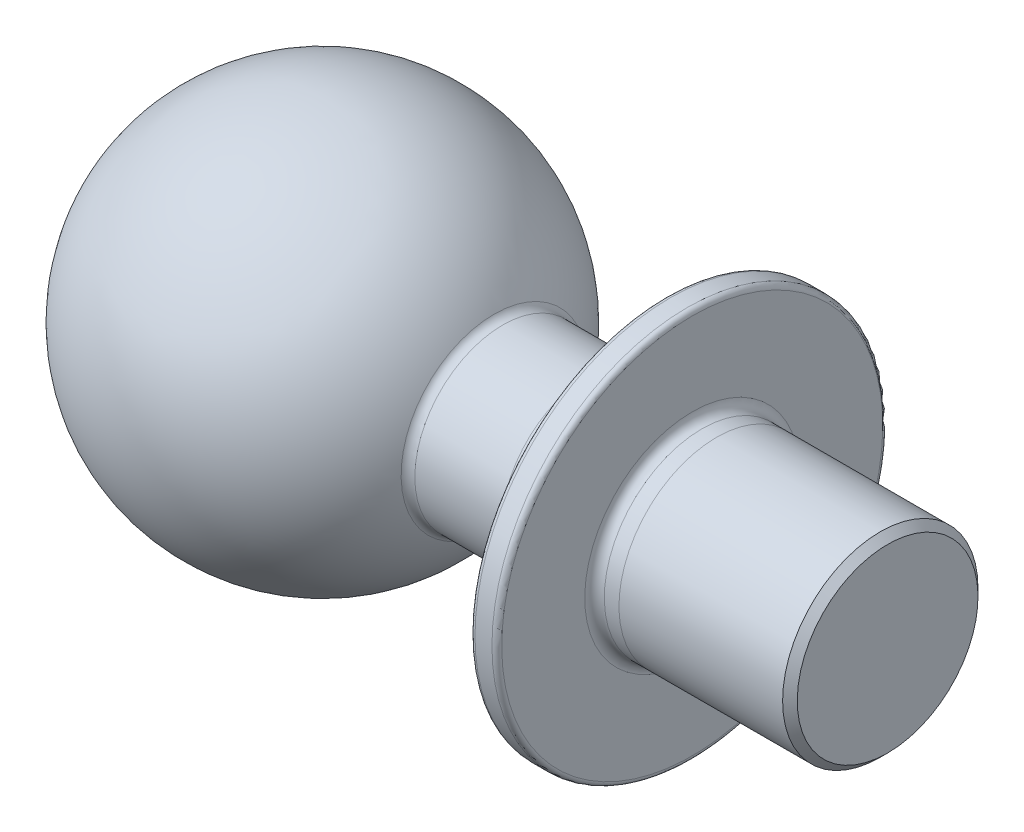
SolidWorks part; units mm, degrees
ref_plane "Front Plane" through (0, 0, 0) normal (0, 0, 1) x (1, 0, 0)
ref_plane "Top Plane" through (0, 0, 0) normal (0, 1, 0) x (1, 0, 0)
ref_plane "Right Plane" through (0, 0, 0) normal (1, 0, 0) x (0, 0, -1)
sketch "Sketch1" plane through (0, 0, 0) normal (0, 0, 1) x (1, 0, 0)
  line L0 (0, 0) -> (0, 1)
  line L1 (0, 1) -> (-2, 1)
  line L2 (-2, 1) -> (-2, 2)
  line L3 (-2, 2) -> (-2.25, 2)
  line L4 (-2.25, 2) -> (-3, 0.9)
  line L5 (-3, 0.9) -> (-4, 0.9)
  line L6 (0, 0) -> (-4, 0)
  line L7 (-4, 0) -> (-7.5845, 0)
  line L8 (-7.5845, 0) -> (-7.5845, 0.875)
  line L9 (-4, 0.9) -> (-4, 0) construction
  line L10 (-7.5845, 0) -> (-7.5845, -0.875) construction
  arc A0 (-7.5845, 0.875) -> (-4, 0.9) centre (-5.7861, 0) cw
  circle A1 centre (-5.7861, 0) radius 2 construction
  dimension "D8" = 4
  dimension "D9" = 2
  dimension "D1" = 1
  dimension "D2" = 2
  dimension "D3" = 1
  dimension "D4" = 0.25
  dimension "D5" = 1
  dimension "D6" = 1
  dimension "D7" = 0.9
  dimension "D10" = 1.75
revolve "Revolve1" add sketch "Sketch1" angle 360 about L6
chamfer "Chamfer1" distance 0.075 angle 45 1 edges at (0, 1, 0)
fillet "Fillet1" radius 0.1 3 edges at (-4, 0.9, 0) (-3, 0.9, 0) (-2, 1, 0)
fillet "Fillet2" radius 0.05 2 edges at (-2, 2, 0) (-2.25, 2, 0)
sketch "Sketch2" plane through (0, 0, 0) normal (0, 0, 1) x (1, 0, 0)
  line L0 (-1.75, 2.6966) -> (-1.75, -2.6319)
  dimension "D1" = 1.75
split line "Split Line1"
sketch "Sketch3" plane through (-7.5845, 0, 0) normal (-1, 0, 0) x (0, 0, 1)
  line L1 (0, 0.664) -> (-0.575, 0.332)
  line L2 (-0.575, 0.332) -> (-0.575, -0.332)
  line L3 (-0.575, -0.332) -> (0, -0.664)
  line L4 (0, -0.664) -> (0.575, -0.332)
  line L5 (0.575, -0.332) -> (0.575, 0.332)
  line L6 (0.575, 0.332) -> (0, 0.664)
  circle A1 centre (0, 0) radius 0.575
  dimension "D2" = 1.15
extrude "Cut-Extrude1" cut sketch "Sketch3" against normal blind 1 contours L6 L1 L2 L3 L4 L5
fillet "Fillet3" radius 0.05 18 edges at (-6.5845, 0, -0.575) (-6.5845, 0.498, -0.2875) (-6.5845, 0.498, 0.2875) (-6.5845, -0.498, 0.2875) (-6.5845, -0.498, -0.2875) (-6.5845, 0, 0.575) (-7.0845, 0.332, 0.575) (-7.0845, 0.664, 0) (-7.0845, 0.332, -0.575) (-7.0845, -0.664, 0) (-7.0845, -0.332, 0.575) (-7.0845, -0.332, -0.575) (-7.5845, 0.498, 0.2875) (-7.5845, 0.498, -0.2875) (-7.5845, 0, -0.575) (-7.5845, -0.498, 0.2875) (-7.5845, 0, 0.575) (-7.5845, -0.498, -0.2875)
